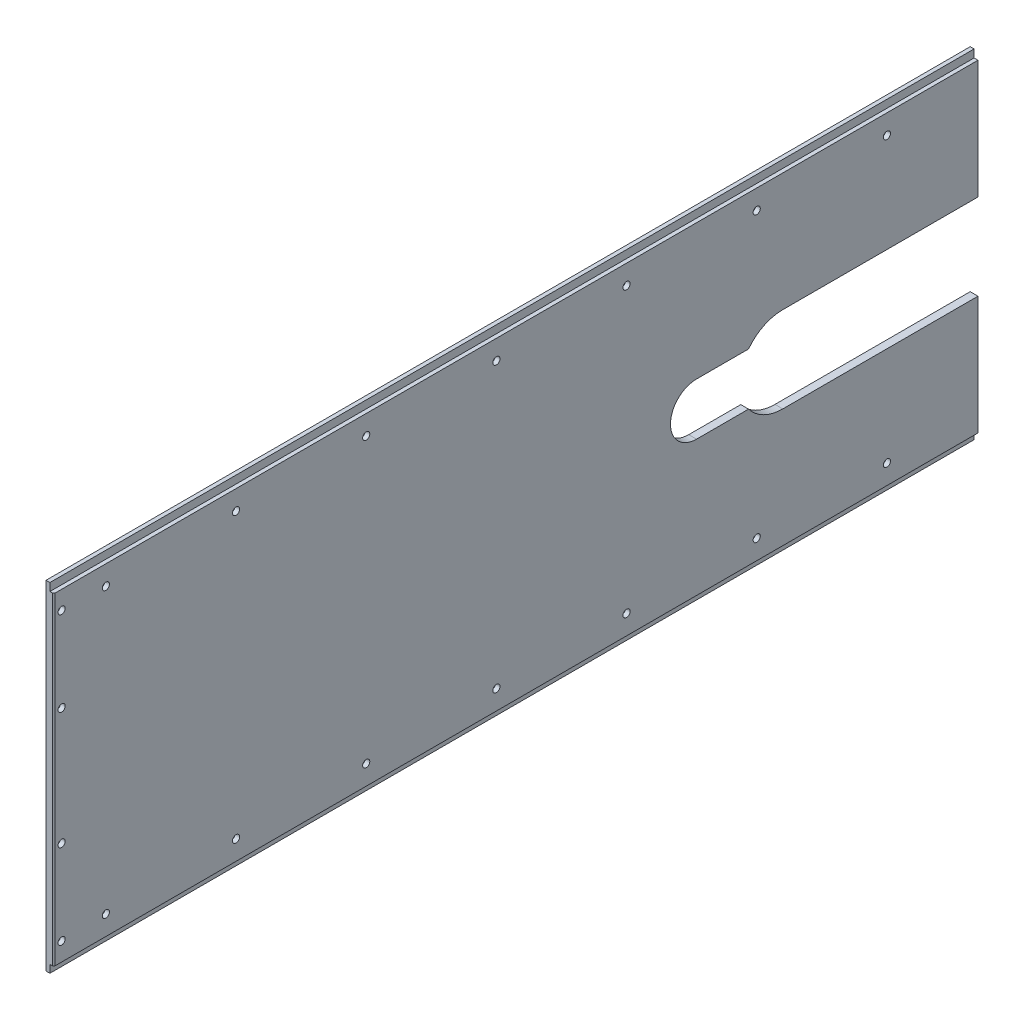
SolidWorks part; units mm, degrees
material "1060 Legierung"
ref_plane "Front Plane" through (0, 0, 0) normal (0, 0, 1) x (1, 0, 0)
ref_plane "Top Plane" through (0, 0, 0) normal (0, 1, 0) x (1, 0, 0)
ref_plane "Right Plane" through (0, 0, 0) normal (1, 0, 0) x (0, 0, -1)
sketch "Sketch1" plane through (0, 0, 0) normal (1, 0, 0) x (0, 0, -1)
  line L0 (0, 0) -> (59.3183, 0) construction
  line L1 (0, 28.1909) -> (0, -28.8956) construction
  line L2 (-355, 130) -> (355, 130)
  line L3 (355, 130) -> (355, 33)
  line L4 (355, -130) -> (-355, -130)
  line L5 (-355, -130) -> (-355, 130)
  line L6 (355, 33) -> (205, 33)
  line L7 (178.7512, -20) -> (138.7512, -20)
  line L8 (355, -33) -> (355, -130)
  line L9 (355, -33) -> (205, -33)
  line L10 (178.7512, 20) -> (138.7512, 20)
  arc A0 (205, 33) -> (178.7512, 20) centre (205, 0) ccw
  arc A1 (138.7512, -20) -> (138.7512, 20) centre (138.7512, 0) cw
  arc A2 (178.7512, -20) -> (205, -33) centre (205, 0) ccw
  dimension "D5" = 20
  dimension "D1" = 710
  dimension "D2" = 260
  dimension "D3" = 150
  dimension "D4" = 66
  dimension "D6" = 40
extrude "Boss-Extrude1" add sketch "Sketch1" along normal blind 6
sketch "Skizze1" plane through (0, 0, 355) normal (0, 0, 1) x (1, 0, 0)
  line L0 (-16.1523, 0) -> (24.9132, 0) construction
  line L1 (3, -130) -> (3, -124)
  line L2 (6, 130) -> (3, 130)
  line L3 (6, 130) -> (6, 124)
  line L4 (6, 124) -> (3, 124)
  line L5 (3, 130) -> (3, 124)
  line L6 (6, -124) -> (3, -124)
  line L7 (6, -130) -> (6, -124)
  line L8 (6, -130) -> (3, -130)
  dimension "D1" = 6
  dimension "D2" = 3
extrude "Schnitt-Linear austragen1" cut sketch "Skizze1" against normal through all
hole_wizard "Formsenkung fur M5 Linsensenkschraube mit Schlitz1" positions "Skizze3" profile "Skizze2" countersink size "M5" standard "Din" end condition through all
sketch "Skizze3" plane through (0, 0, 0) normal (-1, 0, 0) x (0, 0, 1)
  line L0 (230.0399, 0) -> (388.5152, 0) construction
  line L3 (355, 130) -> (355, -130) construction
  point P0 (349, -110)
  point P2 (349, -45)
  dimension "D1" = 45
  dimension "D2" = 110
  dimension "D3" = 6
  dimension "D4" = 6
sketch "Skizze2" plane through (0, -110, 349) normal (0, 1, 0) x (0, 0, 1)
  line L0 (0, 0) -> (0, 6)
  line L1 (0, 6) -> (2.75, 6)
  line L2 (2.75, 6) -> (2.75, 2.45)
  line L3 (2.75, 2.45) -> (5.2, 0)
  line L5 (5.2, 0) -> (0, 0)
  line L6 (-2.75, 2.45) -> (-5.2, 0) construction
  line L11 (0, -6.35) -> (0, 107.95) construction
  dimension "Bohrerdurchmesser" = 5.5
  dimension "Bohrungstiefe" = 6
  dimension "Senkdurchmesser (Oben)" = 10.4
  dimension "Senkwinkel (Oben)" = 90
chamfer "Chamfer1" distance 1 angle 45 1 edges at (6, 0, 355)
hole_wizard "CSK for M5 Countersunk Raised Head Screw1" positions "Sketch3" profile "Sketch2" countersink size "M5" standard "DIN" end condition through all
sketch "Sketch3" plane through (0, 0, 0) normal (-1, 0, 0) x (0, 0, 1)
  line L0 (355, 130) -> (355, -130) construction
  line L1 (355, -130) -> (-355, -130) construction
  point P0 (315, -109)
  dimension "D1" = 40
  dimension "D2" = 21
sketch "Sketch2" plane through (0, -109, 315) normal (0, 1, 0) x (0, 0, 1)
  line L0 (0, 0) -> (0, 6)
  line L1 (0, 6) -> (2.75, 6)
  line L2 (2.75, 6) -> (2.75, 2.45)
  line L3 (2.75, 2.45) -> (5.2, 0)
  line L5 (5.2, 0) -> (0, 0)
  line L6 (-2.75, 2.45) -> (-5.2, 0) construction
  line L11 (0, -6.35) -> (0, 107.95) construction
  dimension "Thru Hole Dia." = 5.5
  dimension "Thru Hole Depth" = 6
  dimension "Near C'Sink Dia." = 10.4
  dimension "Near C'Sink Angle" = 90
pattern_linear "LPattern1" count 7 spacing 100 along (0, 0, -1) of "CSK for M5 Countersunk Raised Head Screw1"
mirror "Spiegeln1" about plane through (0, 0, 0) normal (0, 1, 0) of "LPattern1", "Formsenkung fur M5 Linsensenkschraube mit Schlitz1", "CSK for M5 Countersunk Raised Head Screw1"
